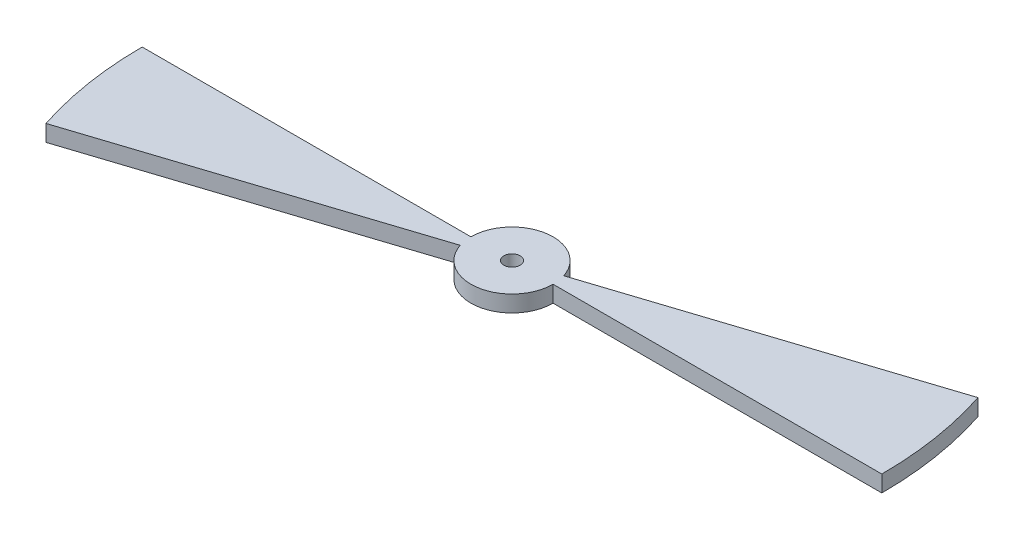
SolidWorks part; units mm, degrees
ref_plane "Front" through (0, 0, 0) normal (0, 0, 1) x (1, 0, 0)
ref_plane "Top" through (0, 0, 0) normal (0, 1, 0) x (1, 0, 0)
ref_plane "Right" through (0, 0, 0) normal (1, 0, 0) x (0, 0, -1)
sketch "草图1" plane through (0, 0, 0) normal (0, 1, 0) x (1, 0, 0)
  line L0 (2.5, 0) -> (22.5, 0)
  line L9 (-2.3776, -0.7725) -> (-21.3988, -6.9529)
  line L10 (-2.5, 0) -> (-22.5, 0)
  line L19 (2.3776, 0.7725) -> (21.3988, 6.9529)
  line L20 (-2.3776, 0.7725) -> (-21.3988, 6.9529) [skipped]
  line L21 (-2.0225, 1.4695) -> (-18.2029, 13.2252) [skipped]
  line L22 (-1.4695, 2.0225) -> (-13.2252, 18.2029) [skipped]
  line L23 (-0.7725, 2.3776) -> (-6.9529, 21.3988) [skipped]
  line L24 (0, 2.5) -> (0, 22.5) [skipped]
  line L25 (0.7725, 2.3776) -> (6.9529, 21.3988) [skipped]
  line L26 (1.4695, 2.0225) -> (13.2252, 18.2029) [skipped]
  line L27 (2.0225, 1.4695) -> (18.2029, 13.2252) [skipped]
  line L28 (-2.0225, -1.4695) -> (-18.2029, -13.2252) [skipped]
  line L29 (-1.4695, -2.0225) -> (-13.2252, -18.2029) [skipped]
  line L30 (-0.7725, -2.3776) -> (-6.9529, -21.3988) [skipped]
  line L31 (0, -2.5) -> (0, -22.5) [skipped]
  line L32 (0.7725, -2.3776) -> (6.9529, -21.3988) [skipped]
  line L33 (1.4695, -2.0225) -> (13.2252, -18.2029) [skipped]
  line L34 (2.0225, -1.4695) -> (18.2029, -13.2252) [skipped]
  line L35 (2.3776, -0.7725) -> (21.3988, -6.9529) [skipped]
  circle A0 centre (0, 0) radius 2.5
  circle A1 centre (0, 0) radius 0.5
  arc A2 (22.5, 0) -> (21.3988, 6.9529) centre (0, 0) ccw
  arc A3 (-22.5, 0) -> (-21.3988, -6.9529) centre (0, 0) ccw
  point P48 (0, 0)
  dimension "D1" = 5
  dimension "D2" = 1
  dimension "D3" = 45
  dimension "D4" = 20
extrude "凸台-拉伸1" add sketch "草图1" along normal blind 1 contours L10 A3 L9 A0 | L0 A2 L19 A0 | A0 A1
